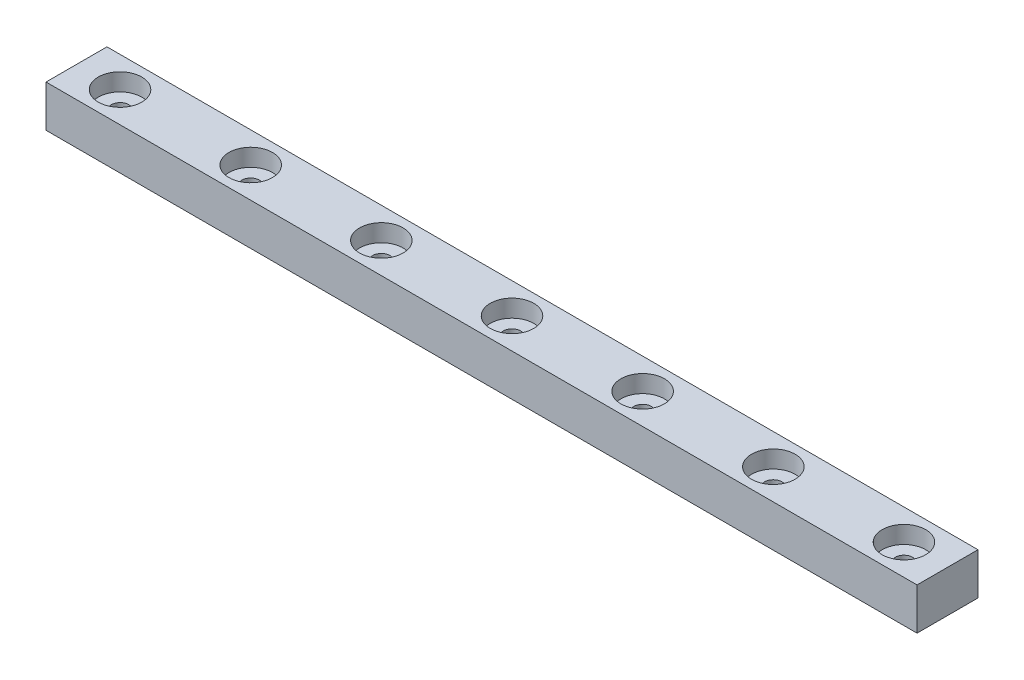
SolidWorks part; units mm, degrees
ref_plane "前视基准面" through (0, 0, 0) normal (0, 0, 1) x (1, 0, 0)
ref_plane "上视基准面" through (0, 0, 0) normal (0, 1, 0) x (1, 0, 0)
ref_plane "右视基准面" through (0, 0, 0) normal (1, 0, 0) x (0, 0, -1)
ref_plane "基准面4" through (0, 4.8, 0) normal (0, 1, 0) x (1, 0, 0)
sketch "草图1" plane through (0, 4.8, 0) normal (0, 1, 0) x (1, 0, 0)
  line L0 (-50, 3.5) -> (-50, -3.5)
  line L1 (-50, -3.5) -> (50, -3.5)
  line L2 (50, -3.5) -> (50, 3.5)
  line L3 (50, 3.5) -> (-50, 3.5)
extrude "凸台-拉伸1" add sketch "草图1" against normal blind 4.8
hole_wizard "M1.6 凹头盖螺钉的柱形沉头孔1" positions "草图3" profile "草图2" counterbore size "M1.6" standard "ANSI Metric"
sketch "草图3" plane through (0, 4.8, 0) normal (0, 1, 0) x (1, 0, 0)
  point P0 (-30, 0)
  point P1 (-15, 0)
  point P2 (0, 0)
  point P3 (15, 0)
  point P4 (30, 0)
  point P5 (45, 0)
  point P6 (-45, 0)
sketch "草图2" plane through (-30, 4.8, 0) normal (1, 0, 0) x (0, 0, 1)
  line L0 (0, 0) -> (0, 4.8)
  line L1 (0, 4.8) -> (1, 4.8)
  line L3 (1, 4.8) -> (1, 2)
  line L4 (1, 2) -> (2.5, 2)
  line L5 (2.5, 2) -> (2.5, 0)
  line L7 (2.5, 0) -> (0, 0)
  line L11 (0, -6.35) -> (0, 107.95) construction
  dimension "通孔孔直径" = 2
  dimension "通孔孔深度" = 4.8
  dimension "柱形沉头孔直径" = 5
  dimension "柱形沉头孔深度" = 2
